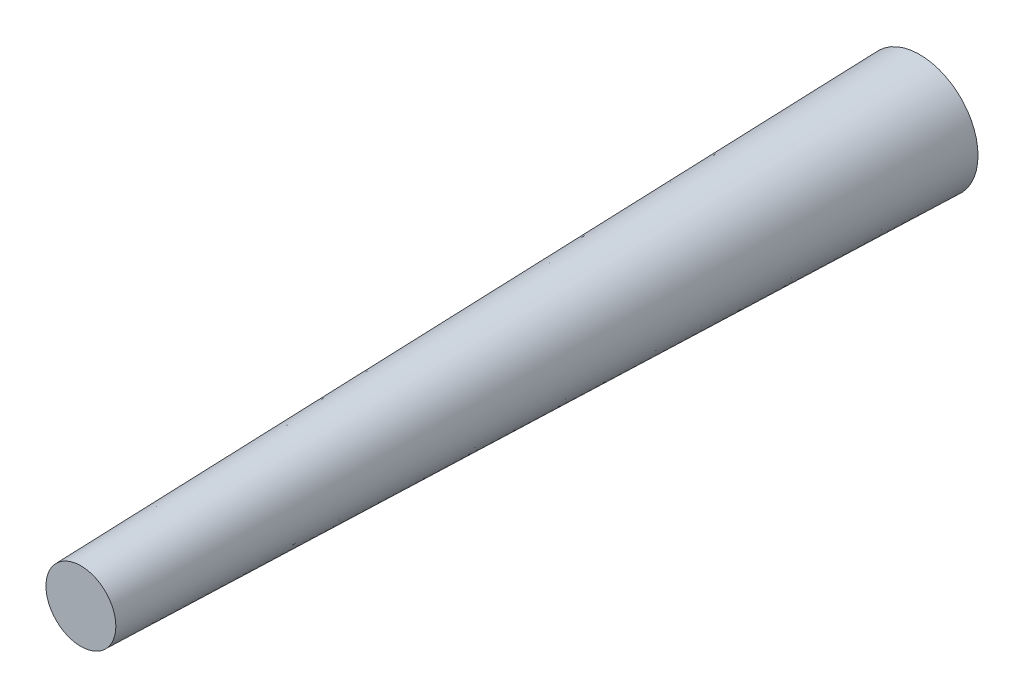
SolidWorks part; units mm, degrees
material "AISI 1045 Steel, cold drawn"
ref_plane "Front Plane" through (0, 0, 0) normal (0, 0, 1) x (1, 0, 0)
ref_plane "Top Plane" through (0, 0, 0) normal (0, 1, 0) x (1, 0, 0)
ref_plane "Right Plane" through (0, 0, 0) normal (1, 0, 0) x (0, 0, -1)
sketch "Sketch1" plane through (0, 0, 0) normal (1, 0, 0) x (0, 0, -1)
  line L0 (-18, 0) -> (18, 0)
  line L1 (18, 0) -> (18.0001, 0)
  line L2 (18.0001, 0) -> (18.0001, 2.5)
  line L3 (-18, 0) -> (-18, 1.5)
  line L4 (18.0001, 2.5) -> (-18, 1.5)
  point P4 (0, 0)
  point P6 (18.0001, 1.25)
  dimension "D1" = 36.0001
  dimension "D2" = 2.5
  dimension "D3" = 1.5
  dimension "D4" = 36
revolve "Revolve1" add sketch "Sketch1" angle 360 about L0
